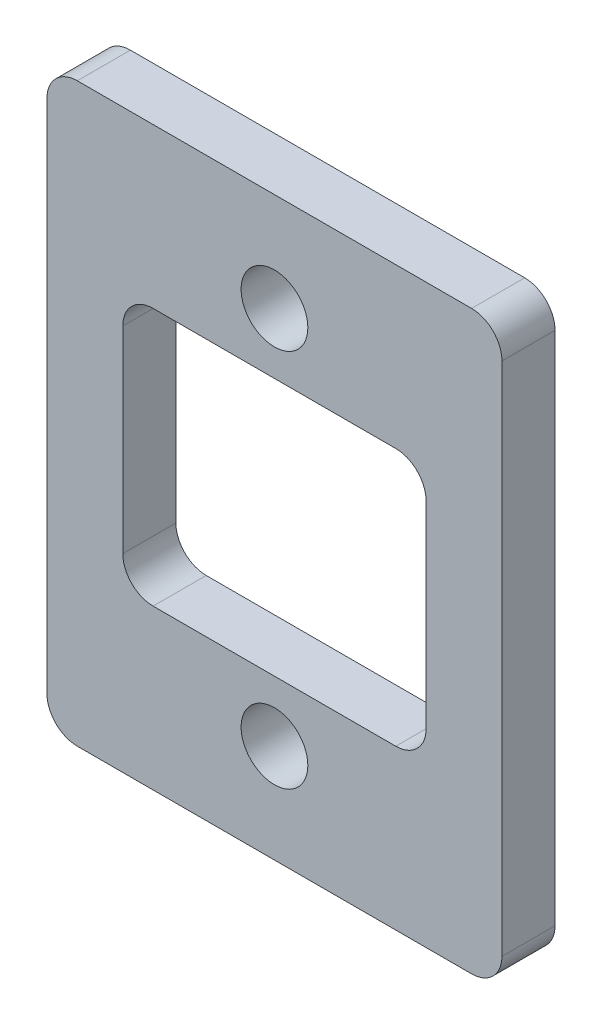
SolidWorks part; units mm, degrees
material "ABS"
ref_plane "前视基准面" through (0, 0, 0) normal (0, 0, 1) x (1, 0, 0)
ref_plane "上视基准面" through (0, 0, 0) normal (0, 1, 0) x (1, 0, 0)
ref_plane "右视基准面" through (0, 0, 0) normal (1, 0, 0) x (0, 0, -1)
sketch "草图1" plane through (0, 0, 0) normal (0, 0, 1) x (1, 0, 0)
  line L1 (-15, -19) -> (15, -19)
  line L2 (-15, -19) -> (-15, 19)
  line L3 (-15, 19) -> (15, 19)
  line L4 (15, -19) -> (15, 19)
  line L5 (0, 19) -> (0, -19) construction
  line L6 (-15, 0) -> (15, 0) construction
  circle A0 centre (0, 12.5) radius 2.2
  circle A1 centre (0, -12.5) radius 2.2
  point P0 (0, 0)
  dimension "D4" = 4.4
  dimension "D1" = 30
  dimension "D2" = 38
  dimension "D3" = 25
extrude "凸台-拉伸1" add sketch "草图1" along normal blind 3.5
sketch "草图2" plane through (0, 0, 3.5) normal (0, 0, 1) x (1, 0, 0)
  line L0 (15, -19) -> (15, 19) construction
  line L1 (-10, -8.5) -> (10, -8.5)
  line L2 (-10, -8.5) -> (-10, 8.5)
  line L3 (-10, 8.5) -> (10, 8.5)
  line L4 (10, -8.5) -> (10, 8.5)
  line L5 (0, 8.5) -> (0, -8.5) construction
  line L6 (-10, 0) -> (10, 0) construction
  circle A0 centre (0, 12.5) radius 2.2 construction
  point P0 (0, 0)
  dimension "D1" = 4
  dimension "D2" = 5
extrude "切除-拉伸1" cut sketch "草图2" against normal blind 10
fillet "圆角1" radius 2 8 edges at (15, -19, 1.75) (-15, -19, 1.75) (-15, 19, 1.75) (15, 19, 1.75) (-10, 8.5, 1.75) (10, 8.5, 1.75) (-10, -8.5, 1.75) (10, -8.5, 1.75)
